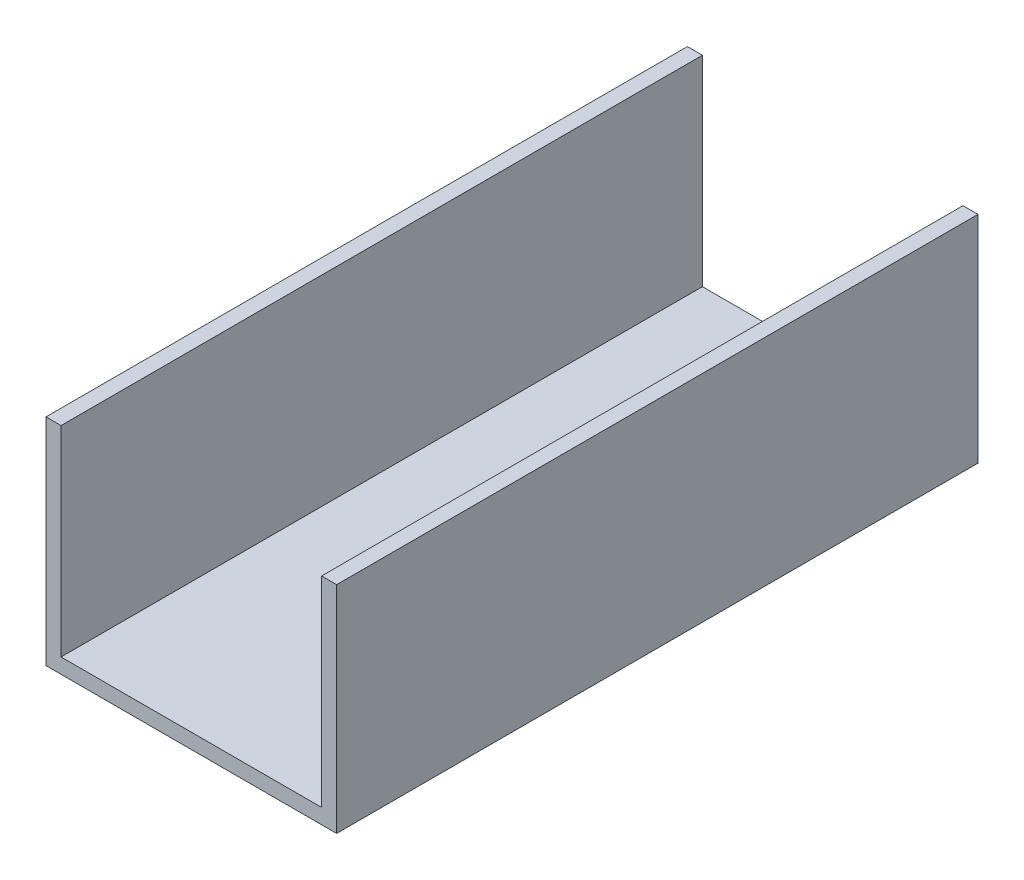
SolidWorks part; units mm, degrees
ref_plane "Front Plane" through (0, 0, 0) normal (0, 0, 1) x (1, 0, 0)
ref_plane "Top Plane" through (0, 0, 0) normal (0, 1, 0) x (1, 0, 0)
ref_plane "Right Plane" through (0, 0, 0) normal (1, 0, 0) x (0, 0, -1)
sketch "Sketch1" plane through (0, 0, 0) normal (0, 0, 1) x (1, 0, 0)
  line L0 (87.3125, 68.2625) -> (92.075, 68.2625)
  line L5 (0, 0) -> (92.075, 0)
  line L6 (0, 0) -> (0, 68.2625)
  line L7 (0, 68.2625) -> (4.7625, 68.2625)
  line L8 (92.075, 0) -> (92.075, 68.2625)
  line L10 (4.7625, 68.2625) -> (4.7625, 4.7625)
  line L11 (4.7625, 4.7625) -> (87.3125, 4.7625)
  line L12 (87.3125, 68.2625) -> (87.3125, 4.7625)
  line L13 (87.3125, 4.7625) -> (87.3125, 0) construction
  dimension "D1" = 82.55
  dimension "D2" = 4.7625
  dimension "D3" = 63.5
extrude "Boss-Extrude1" add sketch "Sketch1" along normal blind 203.2
